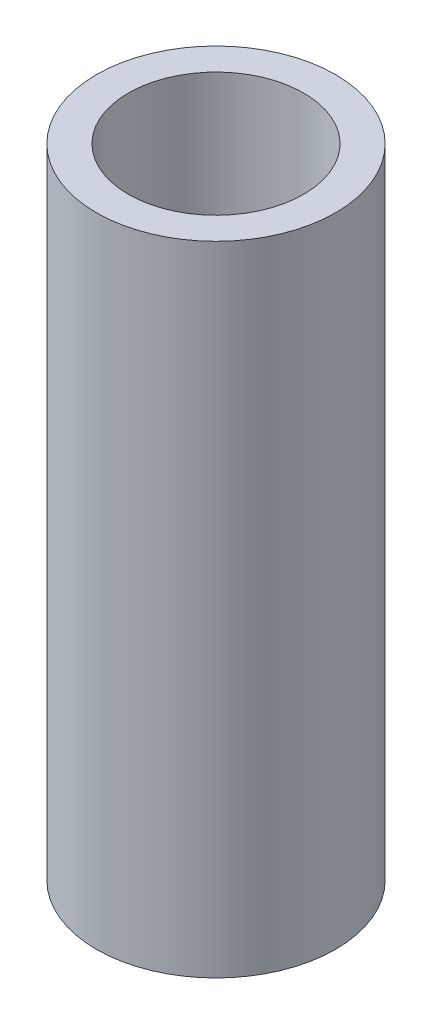
SolidWorks part; units mm, degrees
ref_plane "Front Plane" through (0, 0, 0) normal (0, 0, 1) x (1, 0, 0)
ref_plane "Top Plane" through (0, 0, 0) normal (0, 1, 0) x (1, 0, 0)
ref_plane "Right Plane" through (0, 0, 0) normal (1, 0, 0) x (0, 0, -1)
sketch "Sketch1" plane through (0, 0, 0) normal (0, 1, 0) x (1, 0, 0)
  circle A0 centre (0, 0) radius 2.75
  circle A1 centre (0, 0) radius 3.75
  dimension "D1" = 5.5
  dimension "D2" = 7.5
extrude "Boss-Extrude1" add sketch "Sketch1" along normal blind 20
